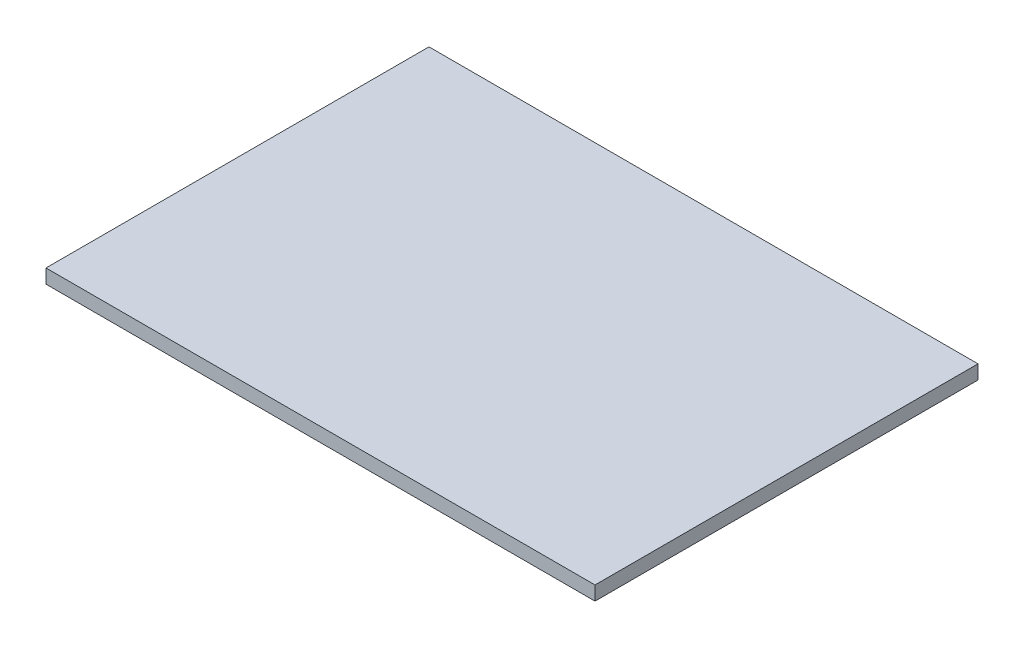
SolidWorks part; units mm, degrees
ref_plane "Front Plane" through (0, 0, 0) normal (0, 0, 1) x (1, 0, 0)
ref_plane "Top Plane" through (0, 0, 0) normal (0, 1, 0) x (1, 0, 0)
ref_plane "Right Plane" through (0, 0, 0) normal (1, 0, 0) x (0, 0, -1)
sketch "Sketch1" plane through (0, 0, 0) normal (0, 1, 0) x (1, 0, 0)
  line L0 (100, 425) -> (100, 75) construction
  line L1 (102, 77) -> (598, 77)
  line L2 (102, 77) -> (102, 423)
  line L3 (102, 423) -> (598, 423)
  line L4 (598, 77) -> (598, 423)
  line L7 (600, 425) -> (100, 425) construction
  line L8 (100, 75) -> (600, 75) construction
  line L9 (600, 75) -> (600, 425) construction
  dimension "D1" = 2
  dimension "D2" = 2
  dimension "D3" = 2
  dimension "D4" = 2
extrude "Boss-Extrude1" add sketch "Sketch1" along normal blind 12.7
ref_plane "Plane1" through (0, 0, -250) normal (0, 0, 1) x (1, 0, 0)
ref_plane "Plane2" through (350, 0, 0) normal (1, 0, 0) x (0, 0, -1)
